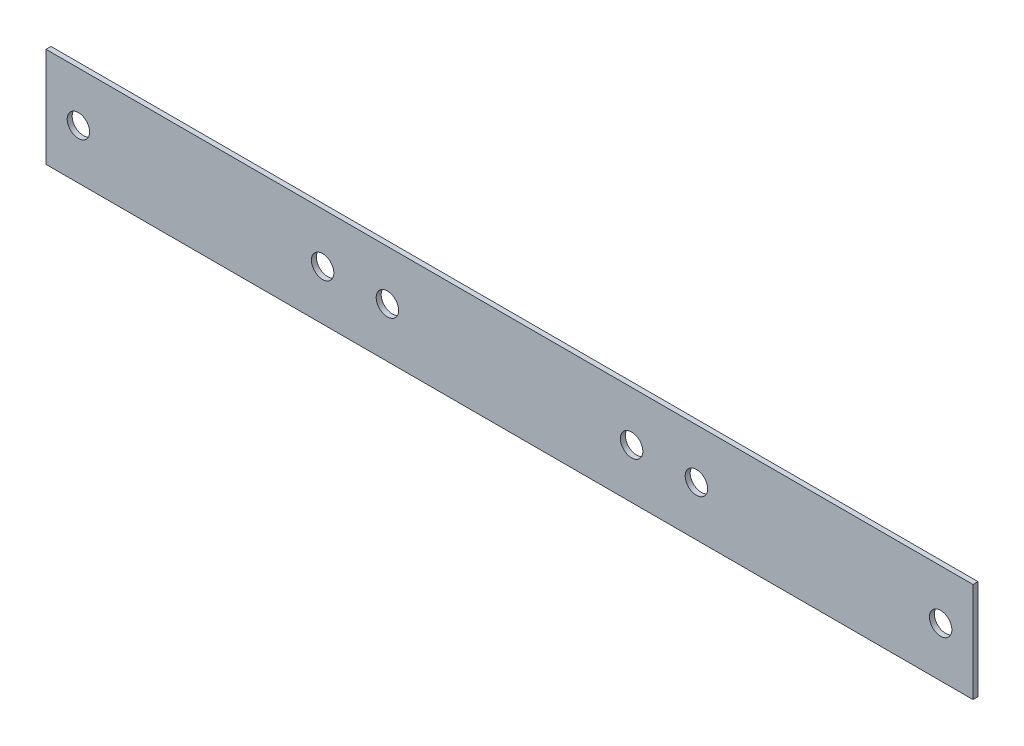
SolidWorks part; units mm, degrees
ref_plane "Front Plane" through (0, 0, 0) normal (0, 0, 1) x (1, 0, 0)
ref_plane "Top Plane" through (0, 0, 0) normal (0, 1, 0) x (1, 0, 0)
ref_plane "Right Plane" through (0, 0, 0) normal (1, 0, 0) x (0, 0, -1)
sketch "M4 backing holes profile" plane through (0, 0, 0) normal (0, 0, 1) x (1, 0, 0)
  line L0 (-99, -10) -> (87, -10)
  line L1 (87, -10) -> (87, 10)
  line L2 (87, 10) -> (-99, 10)
  line L3 (-99, 10) -> (-99, -10)
  circle A0 centre (-92.5, 0) radius 2.25
  circle A1 centre (-43.5, 0) radius 2.25
  circle A2 centre (-30.5, 0) radius 2.25
  circle A3 centre (18.5, 0) radius 2.25
  circle A4 centre (31.5, 0) radius 2.25
  circle A5 centre (80.5, 0) radius 2.25
extrude "M4 backing holes" add sketch "M4 backing holes profile" along normal blind 1
